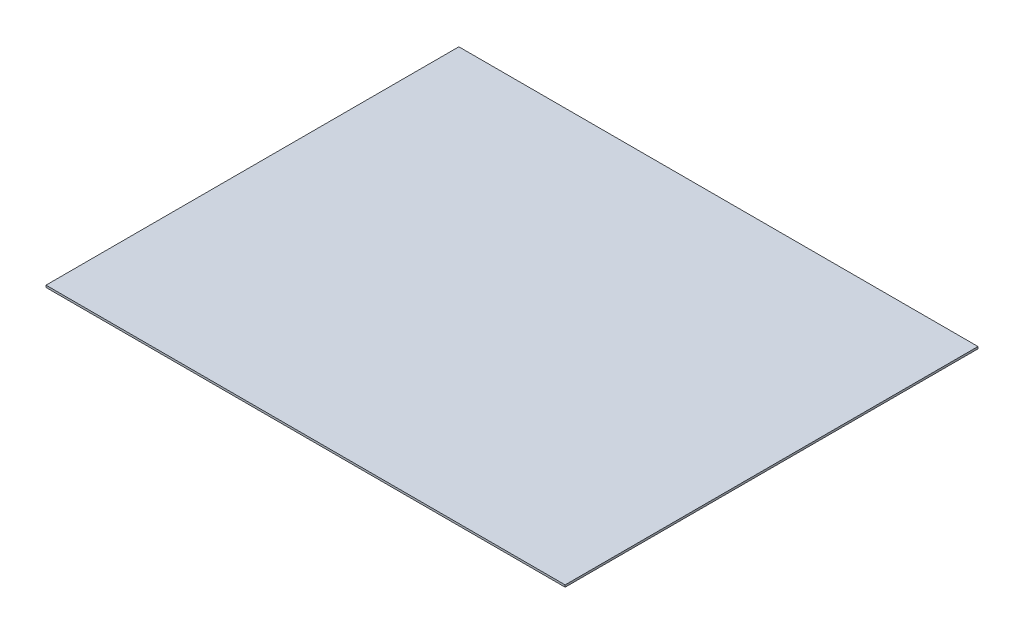
SolidWorks part; units mm, degrees
ref_plane "Front Plane" through (0, 0, 0) normal (0, 0, 1) x (1, 0, 0)
ref_plane "Top Plane" through (0, 0, 0) normal (0, 1, 0) x (1, 0, 0)
ref_plane "Right Plane" through (0, 0, 0) normal (1, 0, 0) x (0, 0, -1)
sketch "Sketch1" plane through (0, 0, 0) normal (0, 1, 0) x (1, 0, 0)
  line L5 (0, 0) -> (645.16, 0)
  line L6 (0, 0) -> (0, 513.08)
  line L7 (0, 513.08) -> (645.16, 513.08)
  line L8 (645.16, 0) -> (645.16, 513.08)
  point P0 (0, 0)
  dimension "D1" = 645.16
  dimension "D2" = 513.08
extrude "Boss-Extrude1" add sketch "Sketch1" along normal blind 2.54 contours L6 L5 L8 L7
